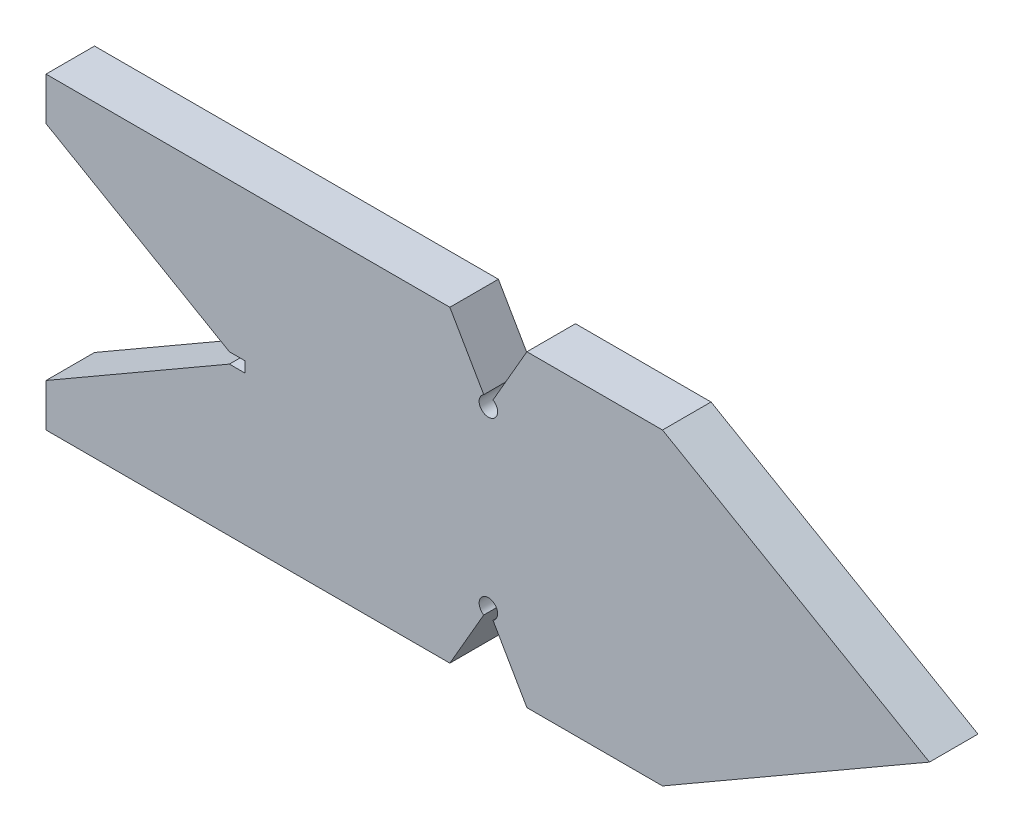
SolidWorks part; units mm, degrees
ref_plane "Front Plane" through (0, 0, 0) normal (0, 0, 1) x (1, 0, 0)
ref_plane "Top Plane" through (0, 0, 0) normal (0, 1, 0) x (1, 0, 0)
ref_plane "Right Plane" through (0, 0, 0) normal (1, 0, 0) x (0, 0, -1)
ref_plane "Plane1" through (0, 0, 0) normal (0, 0, -1) x (-1, 0, 0)
sketch "Sketch1" plane through (0, 0, 0) normal (0, 0, -1) x (-1, 0, 0)
  line L0 (-33.2777, 0) -> (0, 0)
  line L1 (0, 0) -> (0, 3.5346)
  line L2 (0, 3.5346) -> (-15.113, 12.2601)
  line L3 (-15.113, 12.2601) -> (-16.383, 12.2601)
  line L4 (-16.383, 12.2601) -> (-16.383, 13.1399)
  line L5 (-16.383, 13.1399) -> (-15.113, 13.1399)
  line L6 (-15.113, 13.1399) -> (0, 21.8654)
  line L7 (0, 21.8654) -> (0, 25.4)
  line L8 (0, 25.4) -> (-33.2777, 25.4)
  line L9 (-33.2777, 25.4) -> (-36.0717, 20.5607)
  line L10 (-36.8337, 20.5607) -> (-39.6277, 25.4)
  line L11 (-39.6277, 25.4) -> (-50.8, 25.4)
  line L12 (-50.8, 25.4) -> (-72.797, 12.7)
  line L13 (-72.797, 12.7) -> (-50.8, 0)
  line L14 (-50.8, 0) -> (-39.6277, 0)
  line L15 (-39.6277, 0) -> (-36.8337, 4.8393)
  line L16 (-36.0717, 4.8393) -> (-33.2777, 0)
  line L17 (-16.383, 12.7) -> (-72.797, 12.7) construction
  arc A0 (-36.0717, 20.5607) -> (-36.8337, 20.5607) centre (-36.4527, 19.9007) cw
  arc A1 (-36.8337, 4.8393) -> (-36.0717, 4.8393) centre (-36.4527, 5.4993) cw
  dimension "D12" = 0.762
  dimension "D1" = 25.4
  dimension "D2" = 60
  dimension "D3" = 60
  dimension "D4" = 60
  dimension "D5" = 60
  dimension "D6" = 50.8
  dimension "D7" = 3.5346
  dimension "D8" = 0.8799
  dimension "D9" = 6.35
  dimension "D10" = 11.1723
  dimension "D11" = 1.27
extrude "Boss-Extrude1" add sketch "Sketch1" against normal blind 4
sketch "Sketch2" plane through (0, 0, 0) normal (0, 0, -1) x (-1, 0, 0)
  text T0 "60"
extrude "Cut-Extrude1" cut sketch "Sketch2" against normal blind 1
